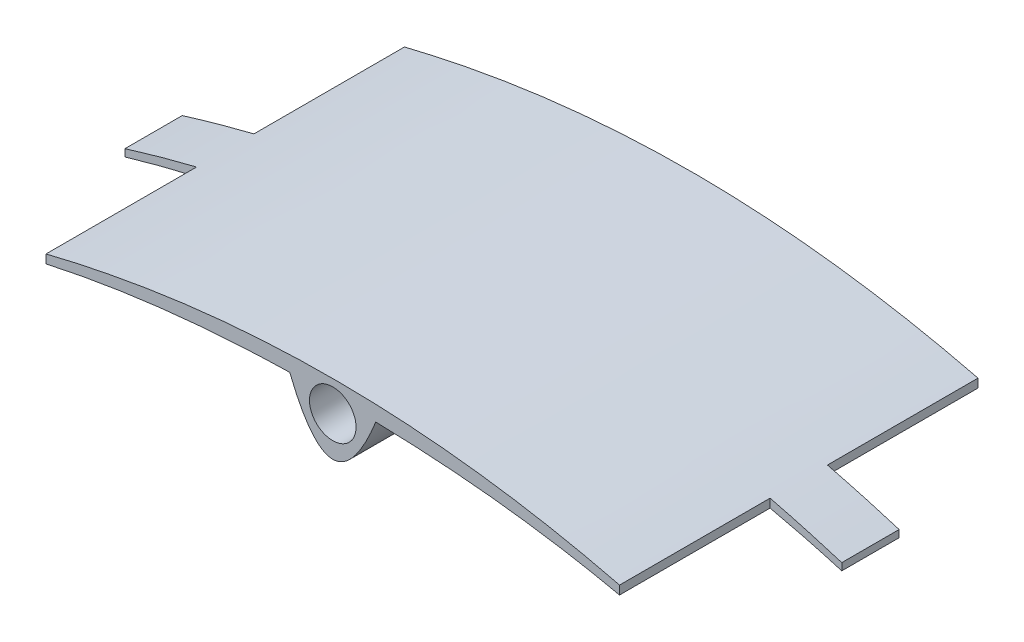
SolidWorks part; units mm, degrees
ref_plane "Front Plane" through (0, 0, 0) normal (0, 0, 1) x (1, 0, 0)
ref_plane "Top Plane" through (0, 0, 0) normal (0, 1, 0) x (1, 0, 0)
ref_plane "Right Plane" through (0, 0, 0) normal (1, 0, 0) x (0, 0, -1)
sketch "草圖1" plane through (0, 0, 0) normal (0, 0, 1) x (1, 0, 0)
  line L0 (-50, -3.4806) -> (0, 12) construction
  line L1 (0, 12) -> (50, -3.4806) construction
  line L2 (-50, -3.4806) -> (-50, -4.4806)
  line L3 (50, -3.4806) -> (50, -4.4806)
  line L4 (-6, 2) -> (0, -13) construction
  line L5 (0, -13) -> (6, 2) construction
  line L6 (6, 2) -> (30, 1.4732) construction
  line L7 (30, 1.4732) -> (50, -4.4806) construction
  line L8 (-6, 2) -> (-30, 1.4732) construction
  line L9 (-30, 1.4732) -> (-50, -4.4806) construction
  circle A0 centre (0, 0) radius 3.25
  spline S0 degree 2 poles (-50, -3.4806) (0, 12) (50, -3.4806) knots 0 0 0 1 1 1
  spline S1 degree 2 poles (-6, 2) (0, -13) (6, 2) knots 0 0 0 1 1 1
  spline S2 degree 2 poles (6, 2) (30, 1.4732) (50, -4.4806) knots 0 0 0 1 1 1
  spline S3 degree 2 poles (-6, 2) (-30, 1.4732) (-50, -4.4806) knots 0 0 0 1 1 1
  point P10 (0, 0)
  point P15 (0, 0)
  dimension "D1" = 6.5
  dimension "D2" = 100
  dimension "D3" = 50
  dimension "D4" = 12
  dimension "D5" = 1
  dimension "D6" = 13
  dimension "D7" = 6
  dimension "D8" = 6
  dimension "D9" = 30
  dimension "D10" = 30
  dimension "D11" = 2
extrude "填料-伸長1" add sketch "草圖1" along normal blind 50
sketch "草圖2" plane through (0, 0, 0) normal (0, 1, 0) x (1, 0, 0)
  line L1 (-50, -50) -> (-40, -50)
  line L2 (-50, -50) -> (-50, -29)
  line L3 (-50, -29) -> (-40, -29)
  line L4 (-40, -50) -> (-40, -29)
  line L5 (-50, 0) -> (-40, 0)
  line L6 (-50, 0) -> (-50, -21)
  line L7 (-50, -21) -> (-40, -21)
  line L8 (-40, 0) -> (-40, -21)
  line L9 (50, 0) -> (40, 0)
  line L10 (50, 0) -> (50, -21)
  line L11 (50, -21) -> (40, -21)
  line L12 (40, 0) -> (40, -21)
  line L13 (50, -50) -> (40, -50)
  line L14 (50, -50) -> (50, -29)
  line L15 (50, -29) -> (40, -29)
  line L16 (40, -50) -> (40, -29)
  dimension "D1" = 10
  dimension "D2" = 21
extrude "除料-伸長1" cut sketch "草圖2" against normal through all and the other way through all
